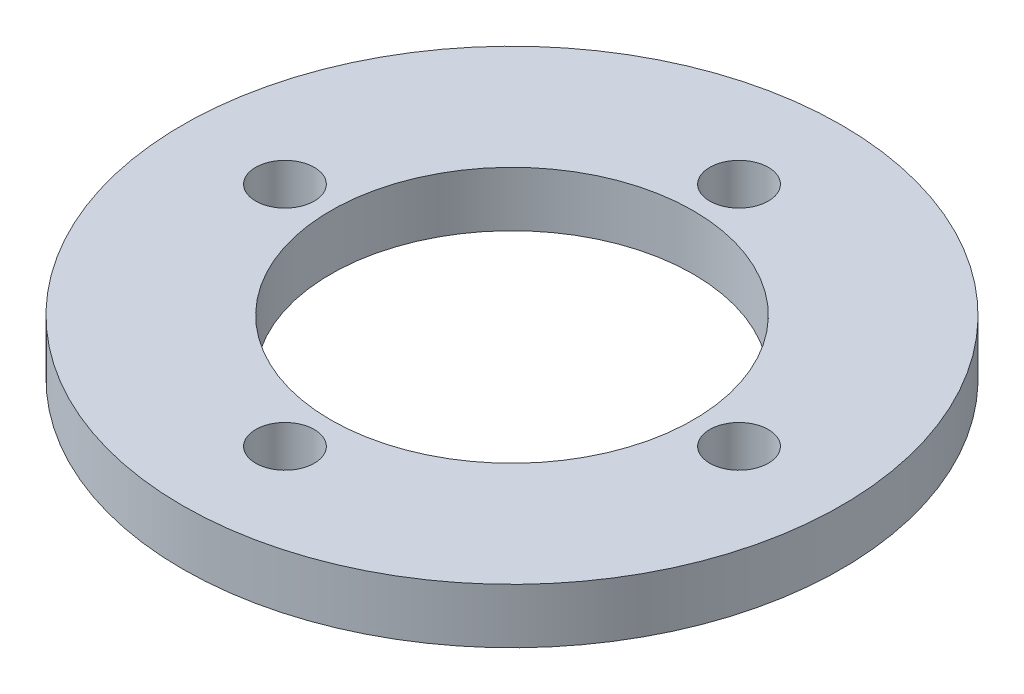
SolidWorks part; units mm, degrees
ref_plane "Front Plane" through (0, 0, 0) normal (0, 0, 1) x (1, 0, 0)
ref_plane "Top Plane" through (0, 0, 0) normal (0, 1, 0) x (1, 0, 0)
ref_plane "Right Plane" through (0, 0, 0) normal (1, 0, 0) x (0, 0, -1)
sketch "Sketch1" plane through (0, 0, 0) normal (0, 1, 0) x (1, 0, 0)
  circle A0 centre (0, 0) radius 9.9
  circle A1 centre (0, 0) radius 18
  circle A2 centre (0, 0) radius 12.4 construction
  circle A3 centre (0, 12.4) radius 1.6
  circle A4 centre (12.4, 0) radius 1.6
  circle A5 centre (0, -12.4) radius 1.6
  circle A6 centre (-12.4, 0) radius 1.6
  point P16 (0, 0)
  dimension "D1" = 19.8
  dimension "D2" = 36
  dimension "D3" = 24.8
  dimension "D4" = 3.2
  dimension "D5" = 4
extrude "Boss-Extrude1" add sketch "Sketch1" along normal blind 3
